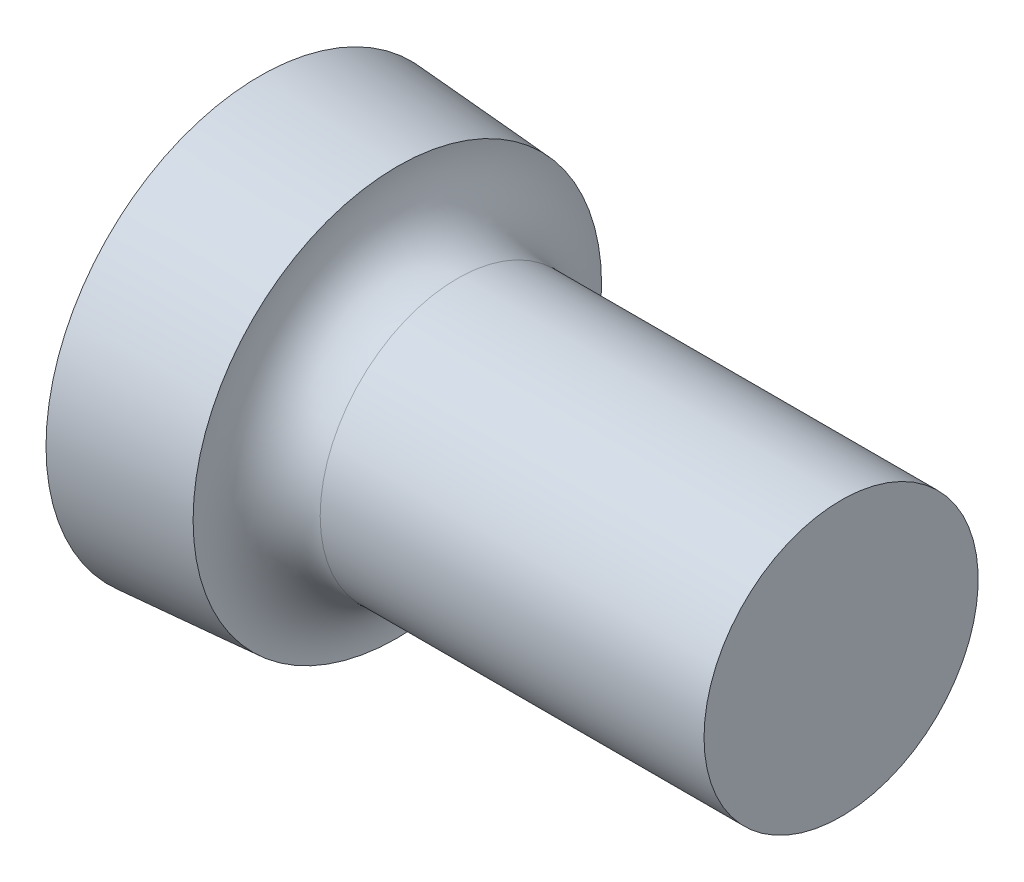
SolidWorks part; units mm, degrees
ref_plane "Płaszczyzna przednia" through (0, 0, 0) normal (0, 0, 1) x (1, 0, 0)
ref_plane "Płaszczyzna górna" through (0, 0, 0) normal (0, 1, 0) x (1, 0, 0)
ref_plane "Płaszczyzna prawa" through (0, 0, 0) normal (1, 0, 0) x (0, 0, -1)
sketch "Szkic1" plane through (0, 0, 0) normal (0, 0, 1) x (1, 0, 0)
  line L0 (0, 0) -> (5.3, 0) construction
  line L1 (0, 0) -> (0, 3.1835) construction
  line L2 (5.3, 0) -> (5.3, 1.25)
  line L3 (5.3, 1.25) -> (1.8, 1.25)
  line L4 (-1.6119, 2.0627) -> (2.478, 1.7767) construction
  line L5 (0, 1.95) -> (1.2535, 1.8623)
  line L6 (0, 1.95) -> (0, 0)
  line L7 (0, 0) -> (5.3, 0)
  arc A0 (1.8, 1.25) -> (1.2535, 1.8623) centre (1.8, 1.8) cw
  point P5 (0, 1.95)
  dimension "D5" = 0.55
  dimension "D1" = 5.3
  dimension "D2" = 1.25
  dimension "D3" = 3.5
  dimension "D4" = 1.95
  dimension "D6" = 4
revolve "Obrót1" add sketch "Szkic1" angle 360 about L7
sketch "Szkic2" plane through (0, 0, 0) normal (0, 0, 1) x (1, 0, 0)
  line L0 (5.3, 1.05) -> (1.8, 1.05) construction
  line L1 (5.3, -1.25) -> (5.3, 1.25) construction
  line L2 (1.8, 1.25) -> (1.8, -1.25) construction
  line L3 (5.3, 1.25) -> (1.8, 1.25) construction
  line L4 (1.2535, 1.8623) -> (1.2535, -1.8623) construction
  line L6 (0, 1.95) -> (0, -1.95) construction
  line L7 (0, 1.75) -> (1.2535, 1.6623) construction
  line L8 (1.2535, 1.8623) -> (0, 0) construction
  line L9 (1.2535, 1.8623) -> (0, 1.95) construction
  point P8 (1.2535, 1.6623)
  point P9 (0, 1.75)
  point P13 (0, 1.95)
  point P18 (0.2, 1.736)
  point P19 (1.125, 1.6713)
  point P25 (0, 0)
  dimension "D1" = 0.2
  dimension "D2" = 0.2
  dimension "D3" = 0.2
  dimension "D4" = 0.2
